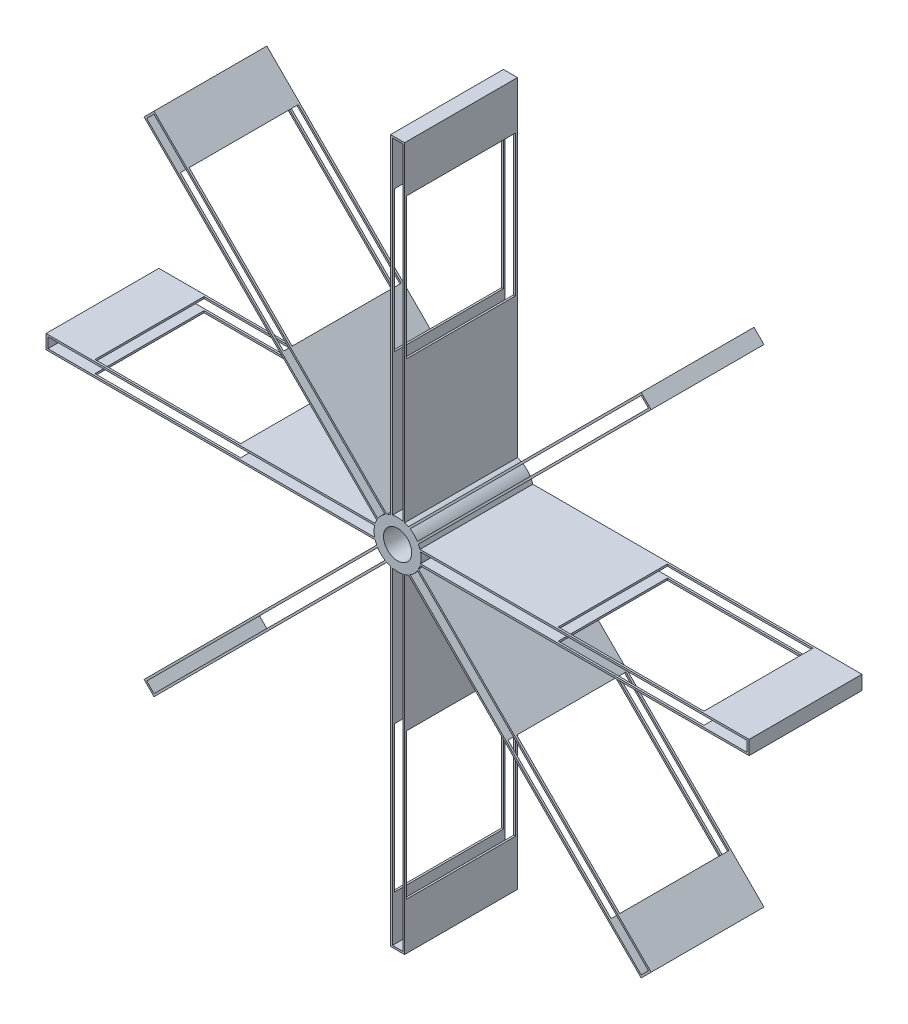
SolidWorks part; units mm, degrees
ref_plane "Front Plane" through (0, 0, 0) normal (0, 0, 1) x (1, 0, 0)
ref_plane "Top Plane" through (0, 0, 0) normal (0, 1, 0) x (1, 0, 0)
ref_plane "Right Plane" through (0, 0, 0) normal (1, 0, 0) x (0, 0, -1)
sketch "Sketch1" plane through (0, 0, 0) normal (0, 0, 1) x (1, 0, 0)
  circle A0 centre (0, 0) radius 25
  dimension "D1" = 50
extrude "Boss-Extrude1" add sketch "Sketch1" along normal blind 120
sketch "Sketch2" plane through (0, 0, 0) normal (0, 0, 1) x (1, 0, 0)
  line L0 (0, 0) -> (0, 33.5538) construction
  line L1 (11.5601, 22.1667) -> (259.0475, 269.6541)
  line L2 (259.0475, 266.8257) -> (13.3555, 21.1337)
  line L3 (-7.5, 23.8485) -> (-7.5, 373.8485)
  line L4 (-7.5, 373.8485) -> (7.5, 373.8485)
  line L5 (7.5, 23.8485) -> (7.5, 373.8485)
  line L6 (22.1667, 11.5601) -> (269.6541, 259.0475)
  line L7 (259.0475, 269.6541) -> (269.6541, 259.0475)
  line L8 (23.8485, 7.5) -> (373.8485, 7.5)
  line L9 (23.8485, -7.5) -> (373.8485, -7.5)
  line L10 (373.8485, 7.5) -> (373.8485, -7.5)
  line L11 (22.1667, -11.5601) -> (269.6541, -259.0475)
  line L12 (11.5601, -22.1667) -> (259.0475, -269.6541)
  line L13 (269.6541, -259.0475) -> (259.0475, -269.6541)
  line L14 (7.5, -23.8485) -> (7.5, -373.8485)
  line L15 (-7.5, -23.8485) -> (-7.5, -373.8485)
  line L16 (7.5, -373.8485) -> (-7.5, -373.8485)
  line L17 (-11.5601, -22.1667) -> (-259.0475, -269.6541)
  line L18 (-22.1667, -11.5601) -> (-269.6541, -259.0475)
  line L19 (-259.0475, -269.6541) -> (-269.6541, -259.0475)
  line L20 (-23.8485, -7.5) -> (-373.8485, -7.5)
  line L21 (-23.8485, 7.5) -> (-373.8485, 7.5)
  line L22 (-373.8485, -7.5) -> (-373.8485, 7.5)
  line L23 (-22.1667, 11.5601) -> (-269.6541, 259.0475)
  line L24 (-11.5601, 22.1667) -> (-259.0475, 269.6541)
  line L25 (-269.6541, 259.0475) -> (-259.0475, 269.6541)
  line L26 (-5.5, 371.8485) -> (5.5, 371.8485)
  line L27 (-5.5, 371.8485) -> (-5.5, 24.3875)
  line L28 (266.8257, 259.0475) -> (21.1337, 13.3555)
  line L29 (5.5, 371.8485) -> (5.5, 24.3875)
  line L30 (259.0475, 266.8257) -> (266.8257, 259.0475)
  line L31 (371.8485, 5.5) -> (24.3875, 5.5)
  line L32 (371.8485, -5.5) -> (24.3875, -5.5)
  line L33 (371.8485, 5.5) -> (371.8485, -5.5)
  line L34 (266.8257, -259.0475) -> (21.1337, -13.3555)
  line L35 (259.0475, -266.8257) -> (13.3555, -21.1337)
  line L36 (266.8257, -259.0475) -> (259.0475, -266.8257)
  line L37 (5.5, -371.8485) -> (5.5, -24.3875)
  line L38 (-5.5, -371.8485) -> (-5.5, -24.3875)
  line L39 (5.5, -371.8485) -> (-5.5, -371.8485)
  line L40 (-259.0475, -266.8257) -> (-13.3555, -21.1337)
  line L41 (-266.8257, -259.0475) -> (-21.1337, -13.3555)
  line L42 (-259.0475, -266.8257) -> (-266.8257, -259.0475)
  line L43 (-371.8485, -5.5) -> (-24.3875, -5.5)
  line L44 (-371.8485, 5.5) -> (-24.3875, 5.5)
  line L45 (-371.8485, -5.5) -> (-371.8485, 5.5)
  line L46 (-266.8257, 259.0475) -> (-21.1337, 13.3555)
  line L47 (-259.0475, 266.8257) -> (-13.3555, 21.1337)
  line L48 (-266.8257, 259.0475) -> (-259.0475, 266.8257)
  circle A0 centre (0, 0) radius 25 construction
  arc A1 (-24.3875, 5.5) -> (-24.3875, -5.5) centre (0, 0) ccw
  arc A2 (-22.1667, 11.5601) -> (-23.8485, 7.5) centre (0, 0) ccw
  arc A3 (-13.3555, 21.1337) -> (-21.1337, 13.3555) centre (0, 0) ccw
  arc A4 (-7.5, 23.8485) -> (-11.5601, 22.1667) centre (0, 0) ccw
  arc A5 (5.5, 24.3875) -> (-5.5, 24.3875) centre (0, 0) ccw
  arc A6 (11.5601, 22.1667) -> (7.5, 23.8485) centre (0, 0) ccw
  arc A7 (21.1337, 13.3555) -> (13.3555, 21.1337) centre (0, 0) ccw
  arc A8 (23.8485, 7.5) -> (22.1667, 11.5601) centre (0, 0) ccw
  arc A9 (24.3875, -5.5) -> (24.3875, 5.5) centre (0, 0) ccw
  arc A10 (22.1667, -11.5601) -> (23.8485, -7.5) centre (0, 0) ccw
  arc A11 (13.3555, -21.1337) -> (21.1337, -13.3555) centre (0, 0) ccw
  arc A12 (7.5, -23.8485) -> (11.5601, -22.1667) centre (0, 0) ccw
  arc A13 (-5.5, -24.3875) -> (5.5, -24.3875) centre (0, 0) ccw
  arc A14 (-11.5601, -22.1667) -> (-7.5, -23.8485) centre (0, 0) ccw
  arc A15 (-21.1337, -13.3555) -> (-13.3555, -21.1337) centre (0, 0) ccw
  arc A16 (-23.8485, -7.5) -> (-22.1667, -11.5601) centre (0, 0) ccw
  point P40 (0, 0)
  point P73 (0, 0)
  dimension "D1" = 15
  dimension "D2" = 7.5
  dimension "D3" = 7.5
  dimension "D4" = 350
  dimension "D6" = 2
  dimension "D7" = 2
  dimension "D8" = 2
  dimension "D9" = 8
  dimension "D5" = 8
extrude "Boss-Extrude3" add sketch "Sketch2" along normal blind 120
sketch "Sketch5" plane through (5.3033, 5.3033, 0) normal (0.7071, 0.7071, 0) x (0, 0, -1)
  line L0 (-120, 373.8485) -> (0, 373.8485) construction
  line L1 (-118, 323.8485) -> (-2, 323.8485)
  line L2 (-118, 323.8485) -> (-118, 168.8485)
  line L3 (-118, 168.8485) -> (-2, 168.8485)
  line L4 (-2, 323.8485) -> (-2, 168.8485)
  line L5 (0, 23.8485) -> (0, 373.8485) construction
  line L6 (-120, 23.8485) -> (-120, 373.8485) construction
  dimension "D1" = 50
  dimension "D2" = 2
  dimension "D3" = 2
  dimension "D4" = 155
extrude "Cut-Extrude1" cut sketch "Sketch5" against normal blind 20
sketch "Sketch6" plane through (-7.5, 0, 0) normal (-1, 0, 0) x (0, 0, 1)
  line L0 (120, 373.8485) -> (0, 373.8485) construction
  line L1 (2, 323.8485) -> (118, 323.8485)
  line L2 (2, 323.8485) -> (2, 173.8485)
  line L3 (2, 173.8485) -> (118, 173.8485)
  line L4 (118, 323.8485) -> (118, 173.8485)
  line L5 (120, 373.8485) -> (120, 23.8485) construction
  line L6 (0, 373.8485) -> (0, 23.8485) construction
  dimension "D1" = 50
  dimension "D2" = 2
  dimension "D3" = 2
  dimension "D4" = 150
extrude "Cut-Extrude2" cut sketch "Sketch6" against normal blind 20
sketch "Sketch7" plane through (5.3033, -5.3033, 0) normal (0.7071, -0.7071, 0) x (0, 0, -1)
  line L0 (-120, 373.8485) -> (0, 373.8485) construction
  line L1 (-118, 323.8485) -> (-2, 323.8485)
  line L2 (-118, 323.8485) -> (-118, 168.8485)
  line L3 (-118, 168.8485) -> (-2, 168.8485)
  line L4 (-2, 323.8485) -> (-2, 168.8485)
  line L5 (0, 11.5601) -> (0, 259.0475) construction
  line L6 (-120, 11.5601) -> (-120, 259.0475) construction
  dimension "D1" = 50
  dimension "D2" = 2
  dimension "D3" = 2
  dimension "D4" = 155
extrude "Cut-Extrude3" cut sketch "Sketch7" against normal blind 20
sketch "Sketch8" plane through (0, -7.5, 0) normal (0, -1, 0) x (1, 0, 0)
  line L0 (-373.8485, 120) -> (-373.8485, 0) construction
  line L1 (-323.8485, 118) -> (-168.8485, 118)
  line L2 (-323.8485, 118) -> (-323.8485, 2)
  line L3 (-323.8485, 2) -> (-168.8485, 2)
  line L4 (-168.8485, 118) -> (-168.8485, 2)
  line L5 (-259.0475, 120) -> (-11.5601, 120) construction
  line L6 (-259.0475, 0) -> (-11.5601, 0) construction
  dimension "D1" = 50
  dimension "D2" = 155
  dimension "D3" = 2
  dimension "D4" = 2
extrude "Cut-Extrude4" cut sketch "Sketch8" against normal blind 20
sketch "Sketch9" plane through (-5.3033, 5.3033, 0) normal (-0.7071, 0.7071, 0) x (0, 0, 1)
  line L0 (120, -373.8485) -> (0, -373.8485) construction
  line L1 (2, -323.8485) -> (116, -323.8485)
  line L2 (2, -323.8485) -> (2, -168.8485)
  line L3 (2, -168.8485) -> (116, -168.8485)
  line L4 (116, -323.8485) -> (116, -168.8485)
  line L6 (118, 22.1667) -> (118, -223.6922) construction
  line L7 (0, -23.8485) -> (0, -373.8485) construction
  dimension "D1" = 50
  dimension "D2" = 155
  dimension "D3" = 2
  dimension "D4" = 2
extrude "Cut-Extrude5" cut sketch "Sketch9" against normal blind 20
sketch "Sketch10" plane through (0, -7.5, 0) normal (0, -1, 0) x (1, 0, 0)
  line L0 (373.8485, 120) -> (373.8485, 0) construction
  line L1 (323.8485, 118) -> (168.8485, 118)
  line L2 (323.8485, 118) -> (323.8485, 2)
  line L3 (323.8485, 2) -> (168.8485, 2)
  line L4 (168.8485, 118) -> (168.8485, 2)
  line L5 (11.5601, 120) -> (259.0475, 120) construction
  line L6 (11.5601, 0) -> (259.0475, 0) construction
  dimension "D1" = 50
  dimension "D2" = 155
  dimension "D3" = 2
  dimension "D4" = 2
extrude "Cut-Extrude6" cut sketch "Sketch10" against normal blind 20
sketch "Sketch12" plane through (-7.5, 0, 0) normal (-1, 0, 0) x (0, 0, 1)
  line L0 (120, -373.8485) -> (0, -373.8485) construction
  line L1 (2, -323.8485) -> (118, -323.8485)
  line L2 (2, -323.8485) -> (2, -168.8485)
  line L3 (2, -168.8485) -> (118, -168.8485)
  line L4 (118, -323.8485) -> (118, -168.8485)
  line L5 (120, -11.5601) -> (120, -259.0475) construction
  line L6 (0, -11.5601) -> (0, -259.0475) construction
  dimension "D1" = 50
  dimension "D2" = 2
  dimension "D3" = 2
  dimension "D4" = 155
extrude "Cut-Extrude7" cut sketch "Sketch12" against normal blind 20
sketch "Sketch13" plane through (-5.3033, -5.3033, 0) normal (-0.7071, -0.7071, 0) x (0, 0, 1)
  line L0 (120, -373.8485) -> (0, -373.8485) construction
  line L1 (2, -323.8485) -> (118, -323.8485)
  line L2 (2, -323.8485) -> (2, -168.8485)
  line L3 (2, -168.8485) -> (118, -168.8485)
  line L4 (118, -323.8485) -> (118, -168.8485)
  line L5 (120, -23.8485) -> (120, -373.8485) construction
  line L6 (0, -23.8485) -> (0, -373.8485) construction
  dimension "D1" = 155
  dimension "D2" = 50
  dimension "D3" = 2
  dimension "D4" = 2
extrude "Cut-Extrude8" cut sketch "Sketch13" against normal blind 20
sketch "Sketch14" plane through (0, 0, 0) normal (0, 0, -1) x (-1, 0, 0)
  circle A0 centre (0, 0) radius 15
  dimension "D1" = 30
extrude "Cut-Extrude11" cut sketch "Sketch14" against normal through all
